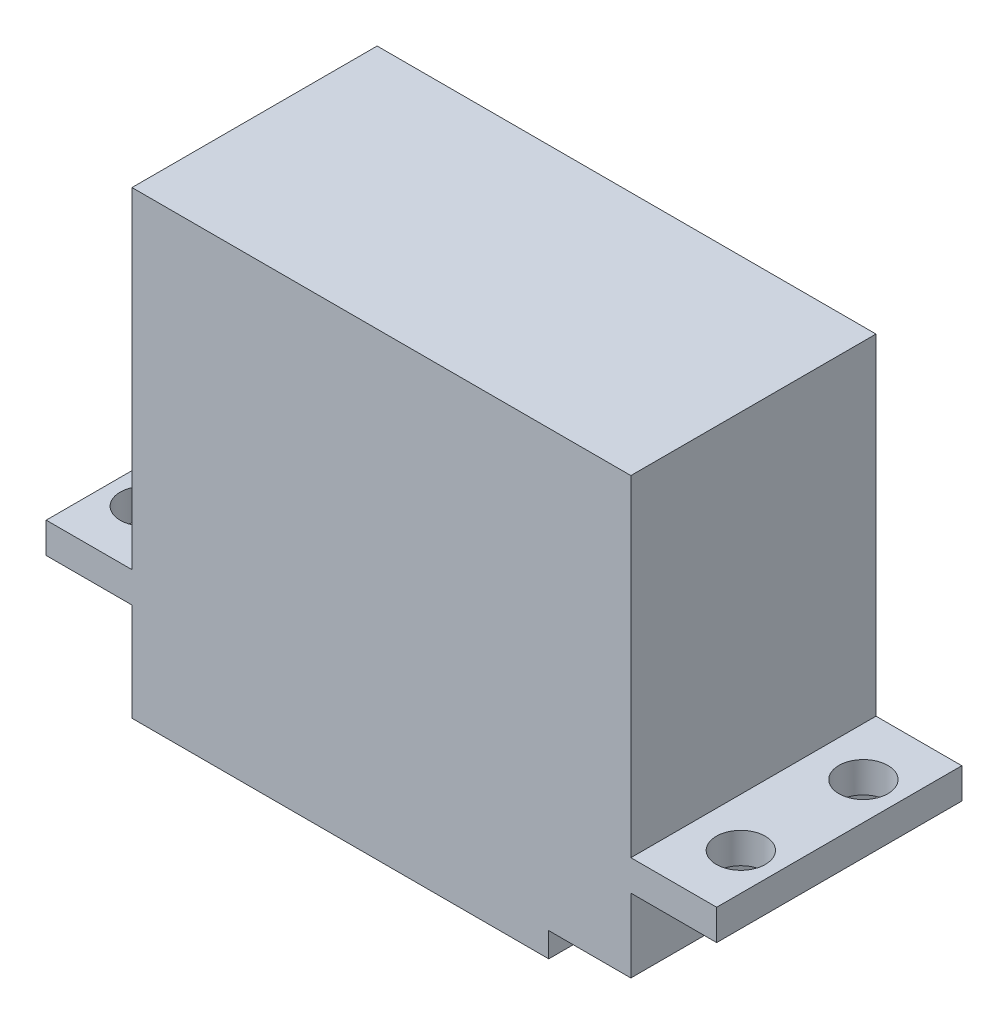
SolidWorks part; units mm, degrees
ref_plane "前视基准面" through (0, 0, 0) normal (0, 0, 1) x (1, 0, 0)
ref_plane "上视基准面" through (0, 0, 0) normal (0, 1, 0) x (1, 0, 0)
ref_plane "右视基准面" through (0, 0, 0) normal (1, 0, 0) x (0, 0, -1)
sketch "草图3" plane through (0, 0, 0) normal (0, 0, 1) x (1, 0, 0)
  line L0 (0, 21.5203) -> (0, -18.1419) construction
  line L1 (-20.35, 16.6554) -> (20.35, 16.6554)
  line L2 (20.35, 16.6554) -> (20.35, -10.3446)
  line L3 (20.35, -10.3446) -> (27.35, -10.3446)
  line L4 (27.35, -10.3446) -> (27.35, -12.8446)
  line L5 (27.35, -12.8446) -> (20.35, -12.8446)
  line L6 (20.35, -12.8446) -> (20.35, -18.8446)
  line L7 (20.35, -18.8446) -> (-20.35, -18.8446)
  line L8 (-20.35, -12.8446) -> (-20.35, -18.8446)
  line L9 (-27.35, -12.8446) -> (-20.35, -12.8446)
  line L10 (-27.35, -10.3446) -> (-27.35, -12.8446)
  line L11 (-20.35, -10.3446) -> (-27.35, -10.3446)
  line L12 (-20.35, 16.6554) -> (-20.35, -10.3446)
  point P12 (0, -18.8446)
  point P17 (0, 16.6554)
  dimension "D1" = 2.5
  dimension "D2" = 7
  dimension "D3" = 40.7
  dimension "D4" = 27
  dimension "D5" = 6
extrude "凸台-拉伸1" add sketch "草图3" along normal blind 20
sketch "草图4" plane through (0, -18.8446, 0) normal (0, -1, 0) x (1, 0, 0)
  line L0 (-20.35, 0) -> (20.35, 0) construction
  line L1 (-20.35, 20) -> (13.65, 20)
  line L2 (-20.35, 20) -> (-20.35, 0)
  line L3 (-20.35, 0) -> (13.65, 0)
  line L4 (13.65, 20) -> (13.65, 0)
  dimension "D1" = 34
extrude "凸台-拉伸2" add sketch "草图4" along normal blind 2
sketch "草图5" plane through (0, -20.8446, 0) normal (0, -1, 0) x (1, 0, 0)
  circle A0 centre (-10.365, 10) radius 6.5
extrude "凸台-拉伸3" add sketch "草图5" along normal blind 1.5
sketch "草图6" plane through (0, -22.3446, 0) normal (0, -1, 0) x (1, 0, 0)
  circle A0 centre (-10.365, 10) radius 2.75
  dimension "D1" = 5.5
extrude "凸台-拉伸4" add sketch "草图6" along normal blind 4
sketch "草图7" plane through (0, -10.3446, 0) normal (0, 1, 0) x (1, 0, 0)
  line L1 (-26.3907, -9.9935) -> (30.3225, -9.9935) construction
  line L2 (0, -24.4219) -> (0, 3.8955) construction
  circle A0 centre (-24.315, -4.9935) radius 2
  circle A1 centre (24.315, -4.9935) radius 2
  circle A2 centre (24.315, -14.9935) radius 2
  circle A3 centre (-24.315, -14.9935) radius 2
  dimension "D1" = 4
  dimension "D2" = 48.63
  dimension "D3" = 10
extrude "切除-拉伸1" cut sketch "草图7" against normal through all
